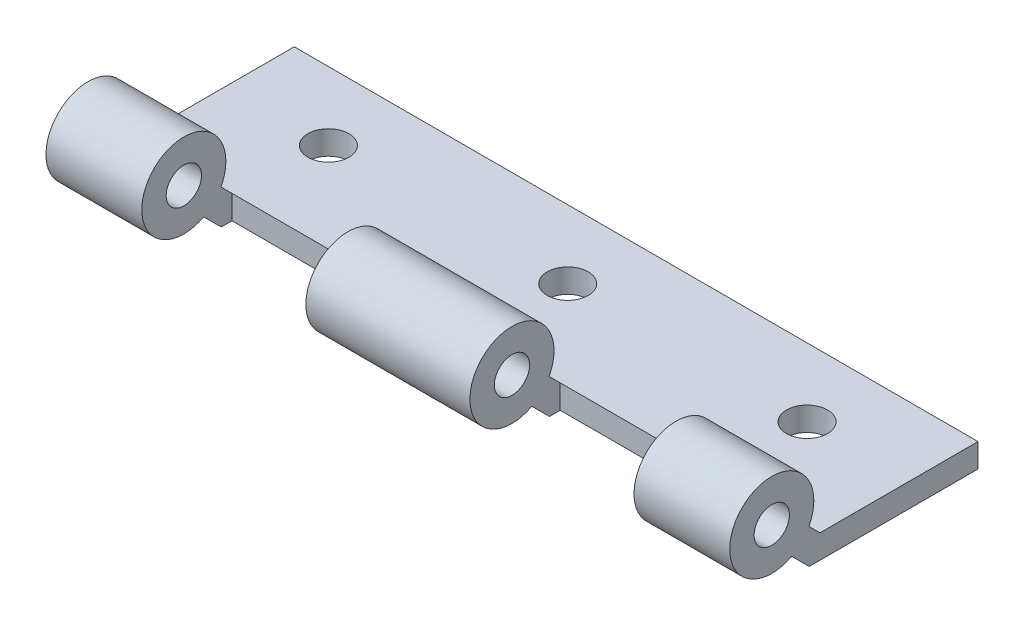
SolidWorks part; units mm, degrees
ref_plane "Front" through (0, 0, 0) normal (0, 0, 1) x (1, 0, 0)
ref_plane "Top" through (0, 0, 0) normal (0, 1, 0) x (1, 0, 0)
ref_plane "Right" through (0, 0, 0) normal (1, 0, 0) x (0, 0, -1)
sketch "Sketch1" plane through (0, 0, 0) normal (1, 0, 0) x (0, 0, -1)
  line L0 (-5.4743, -8) -> (-2.8996, -5.4253)
  line L2 (-30.1625, -4.5202) -> (-7.0459, -4.5202)
  line L3 (-5.4743, -8) -> (-30.1625, -8)
  line L4 (-30.1625, -4.5202) -> (-30.1625, -8)
  line L5 (-7.0459, -4.5202) -> (-5.4253, -2.8996)
  line L6 (-30.1625, -8) -> (30.1625, -8) construction
  line L7 (0, 0) -> (-6.2601, -6.2601) construction
  line L8 (-6.2601, -6.2601) -> (-30.1625, -6.2601) construction
  line L9 (-7.0459, -4.5202) -> (-5.4743, -8) construction
  circle A0 centre (0, 0) radius 2.5797
  arc A2 (-2.8996, -5.4253) -> (-5.4253, -2.8996) centre (0, 0) ccw
  point P1 (0, -8)
  dimension "D1" = 3.5719
  dimension "Pin Dia" = 5.1594
  dimension "D2" = 12.3031
  dimension "Th" = 3.4798
  dimension "D3" = 8
  dimension "Open Wd" = 60.325
  dimension "D4" = 45
sketch "Sketch3" plane through (0, 0, 0) normal (1, 0, 0) x (0, 0, -1)
  line L0 (0, 15.7543) -> (0, -15.7543) construction
  line L1 (5.4743, -8) -> (30.1625, -8)
  line L2 (-30.1625, -8) -> (30.1625, -8) construction
  line L4 (30.1625, -8) -> (30.1625, -4.5202)
  line L5 (30.1625, -4.5202) -> (7.0459, -4.5202)
  line L6 (5.4253, -2.8996) -> (7.0459, -4.5202)
  line L7 (5.4743, -8) -> (2.8996, -5.4253)
  line L9 (-5.4743, -8) -> (-30.1625, -8) construction
  line L10 (-5.4743, -8) -> (-2.8996, -5.4253) construction
  line L11 (-30.1625, -4.5202) -> (-7.0459, -4.5202) construction
  line L13 (-30.1625, -4.5202) -> (-30.1625, -8) construction
  line L14 (-7.0459, -4.5202) -> (-5.4253, -2.8996) construction
  arc A2 (-2.8996, -5.4253) -> (-5.4253, -2.8996) centre (0, 0) ccw construction
  arc A3 (2.8996, -5.4253) -> (5.4253, -2.8996) centre (0, 0) cw
  circle A4 centre (0, 0) radius 2.5797
  circle A5 centre (0, 0) radius 2.5797 construction
extrude "Right Leaf" add sketch "Sketch3" along normal mid plane 100.013 separate body
sketch "Sketch11" plane through (0, -4.5202, 0) normal (0, 1, 0) x (1, 0, 0)
  line L0 (-50.0065, 20.1625) -> (50.0065, 20.1625) construction
  line L1 (-50.0065, 30.1625) -> (-50.0065, 7.0459) construction
  line L2 (50.0065, 30.1625) -> (50.0065, 7.0459) construction
  line L3 (50.0065, 30.1625) -> (-50.0065, 30.1625) construction
  line L4 (-15.0065, 20.1625) -> (85.0065, 20.1625) construction
  line L5 (19.9935, 20.1625) -> (120.0065, 20.1625) construction
  circle A0 centre (-35.0065, 20.1625) radius 3
  circle A1 centre (-0.0065, 20.1625) radius 3
  circle A2 centre (34.9935, 20.1625) radius 3
  dimension "D2" = 6
  dimension "D1" = 10
  dimension "D3" = 15
  dimension "D4" = 3
extrude "Cut-Extrude1" cut sketch "Sketch11" against normal blind 10
ref_plane "Plane1" through (36.0065, 0, 0) normal (1, 0, 0) x (0, 0, -1)
ref_plane "Plane2" through (12.0065, 0, 0) normal (1, 0, 0) x (0, 0, -1)
ref_plane "Plane3" through (-11.9935, 0, 0) normal (-1, 0, 0) x (0, 0, 1)
ref_plane "Plane4" through (12.0065, 0, 0) normal (-1, 0, 0) x (0, 0, 1)
sketch "Sketch12" plane through (36.0065, 0, 0) normal (1, 0, 0) x (0, 0, -1)
  line L0 (2.8996, -5.4253) -> (5.4743, -8)
  line L1 (5.4253, -2.8996) -> (7.0459, -4.5202)
  line L2 (7.0459, -4.5202) -> (7.0459, -8)
  line L3 (5.4743, -8) -> (30.1625, -8) construction
  line L4 (7.0459, -8) -> (5.4743, -8)
  arc A0 (5.4253, -2.8996) -> (2.8996, -5.4253) centre (0, 0) ccw
extrude "Cut-Extrude2" cut sketch "Sketch12" against normal blind 24
sketch "Sketch14" plane through (-11.9935, 0, 0) normal (-1, 0, 0) x (0, 0, 1)
  line L0 (-5.4253, -2.8996) -> (-7.0459, -4.5202)
  line L1 (-7.0459, -4.5202) -> (-7.0459, -8)
  line L2 (-5.4743, -8) -> (-30.1625, -8) construction
  line L3 (-7.0459, -8) -> (-5.4743, -8)
  line L4 (-5.4743, -8) -> (-2.8996, -5.4253)
  arc A0 (-2.8996, -5.4253) -> (-5.4253, -2.8996) centre (0, 0) ccw
extrude "Cut-Extrude5" cut sketch "Sketch14" along normal blind 24
